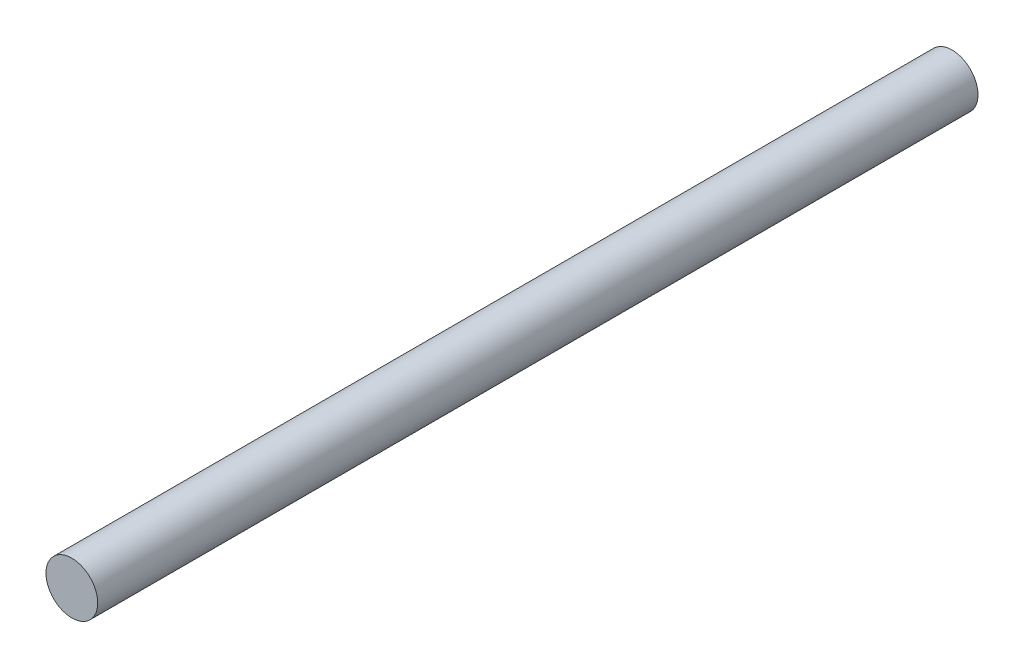
SolidWorks part; units mm, degrees
ref_plane "前视基准面" through (0, 0, 0) normal (0, 0, 1) x (1, 0, 0)
ref_plane "上视基准面" through (0, 0, 0) normal (0, 1, 0) x (1, 0, 0)
ref_plane "右视基准面" through (0, 0, 0) normal (1, 0, 0) x (0, 0, -1)
sketch "草图1" plane through (0, 0, 0) normal (0, 0, 1) x (1, 0, 0)
  circle A0 centre (0, 0) radius 4
  dimension "D1" = 8
extrude "凸台-拉伸1" add sketch "草图1" along normal blind 136
